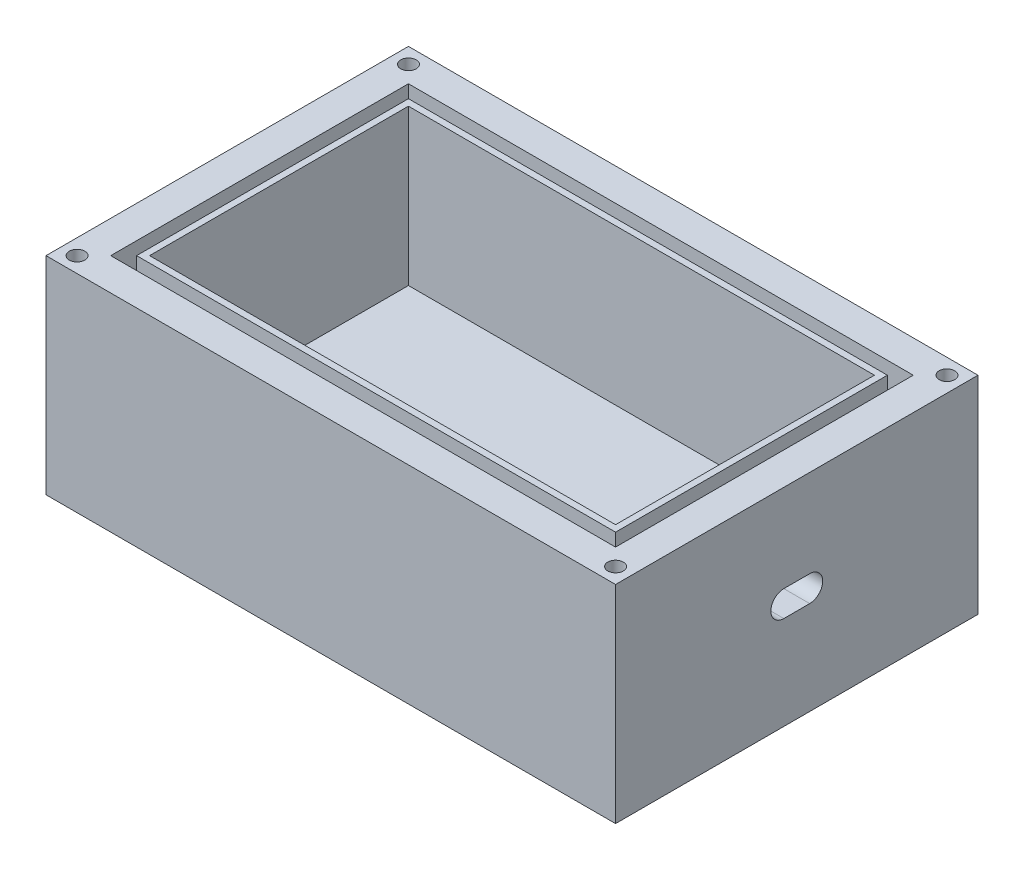
SolidWorks part; units mm, degrees
ref_plane "Front Plane" through (0, 0, 0) normal (0, 0, 1) x (1, 0, 0)
ref_plane "Top Plane" through (0, 0, 0) normal (0, 1, 0) x (1, 0, 0)
ref_plane "Right Plane" through (0, 0, 0) normal (1, 0, 0) x (0, 0, -1)
sketch "Sketch1" plane through (0, 0, 0) normal (0, 1, 0) x (1, 0, 0)
  line L1 (-69.85, 44.45) -> (69.85, 44.45)
  line L2 (-69.85, 44.45) -> (-69.85, -44.45)
  line L3 (-69.85, -44.45) -> (69.85, -44.45)
  line L4 (69.85, 44.45) -> (69.85, -44.45)
  line L5 (-69.85, 44.45) -> (69.85, -44.45) construction
  line L6 (-69.85, -44.45) -> (69.85, 44.45) construction
  point P0 (0, 0)
  dimension "D1" = 139.7
  dimension "D2" = 88.9
extrude "Boss-Extrude1" add sketch "Sketch1" along normal blind 50.8
sketch "Sketch3" plane through (0, 50.8, 0) normal (0, 1, 0) x (1, 0, 0)
  line L1 (-57.15, 31.75) -> (57.15, 31.75)
  line L2 (-57.15, 31.75) -> (-57.15, -31.75)
  line L3 (-57.15, -31.75) -> (57.15, -31.75)
  line L4 (57.15, 31.75) -> (57.15, -31.75)
  line L5 (-57.15, 31.75) -> (57.15, -31.75) construction
  line L6 (-57.15, -31.75) -> (57.15, 31.75) construction
  point P0 (0, 0)
  dimension "D1" = 114.3
  dimension "D2" = 63.5
extrude "Cut-Extrude1" cut sketch "Sketch3" against normal blind 38.1
sketch "Sketch6" plane through (0, 50.8, 0) normal (0, 1, 0) x (1, 0, 0)
  line L0 (-58.7375, 33.3375) -> (-58.7375, -33.3375)
  line L1 (-58.7375, -33.3375) -> (58.7375, -33.3375)
  line L2 (58.7375, -33.3375) -> (58.7375, 33.3375)
  line L3 (58.7375, 33.3375) -> (-58.7375, 33.3375)
  line L4 (-27.94, 0) -> (27.94, 0) construction
  line L5 (0, -27.94) -> (0, 27.94) construction
  line L6 (-61.9125, 36.5125) -> (-61.9125, -36.5125)
  line L7 (-61.9125, -36.5125) -> (61.9125, -36.5125)
  line L8 (61.9125, -36.5125) -> (61.9125, 36.5125)
  line L9 (61.9125, 36.5125) -> (-61.9125, 36.5125)
  dimension "D1" = 117.475
  dimension "D2" = 66.675
  dimension "D3" = 33.3375
  dimension "D4" = 58.7375
  dimension "D5" = 123.825
  dimension "D6" = 73.025
  dimension "D7" = 61.9125
  dimension "D8" = 36.5125
extrude "Cut-Extrude2" cut sketch "Sketch6" against normal blind 6.35
sketch "Sketch7" plane through (0, 50.8, 0) normal (0, 1, 0) x (1, 0, 0)
  circle A0 centre (-66.04, 40.64) radius 1.905
  point P0 (0, 0)
  dimension "D1" = 3.81
extrude "Cut-Extrude3" cut sketch "Sketch7" against normal blind 12.7
mirror "Mirror1" about plane through (0, 0, 0) normal (1, 0, 0) of "Cut-Extrude3"
mirror "Mirror2" about plane through (0, 0, 0) normal (0, 0, 1) of "Mirror1", "Cut-Extrude3"
sketch "Sketch9" plane through (69.85, 0, 0) normal (1, 0, 0) x (0, 0, -1)
  line L0 (-3.175, 22.9267) -> (3.175, 22.9267)
  line L1 (-3.175, 29.2767) -> (3.175, 29.2767)
  line L2 (0, 27.94) -> (0, -27.94) construction
  arc A0 (3.175, 22.9267) -> (3.175, 29.2767) centre (3.175, 26.1017) ccw
  arc A1 (-3.175, 29.2767) -> (-3.175, 22.9267) centre (-3.175, 26.1017) ccw
  dimension "D1" = 6.35
  dimension "D2" = 6.35
  dimension "D3" = 6.35
  dimension "D4" = 3.175
extrude "Cut-Extrude5" cut sketch "Sketch9" against normal up to surface (12.7 mm away) up to face at (57.15, 31.75, 0)
